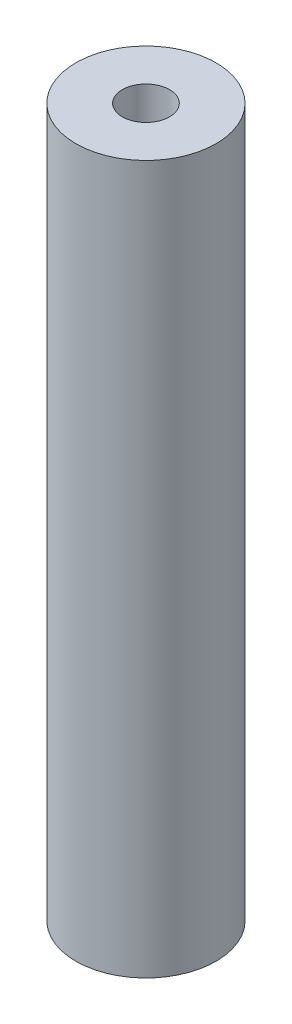
SolidWorks part; units mm, degrees
ref_plane "Front Plane" through (0, 0, 0) normal (0, 0, 1) x (1, 0, 0)
ref_plane "Top Plane" through (0, 0, 0) normal (0, 1, 0) x (1, 0, 0)
ref_plane "Right Plane" through (0, 0, 0) normal (1, 0, 0) x (0, 0, -1)
sketch "Sketch1" plane through (0, 0, 0) normal (0, 1, 0) x (1, 0, 0)
  circle A0 centre (0, 0) radius 2.97
  circle A1 centre (0, 0) radius 1
  dimension "D1" = 5.94
  dimension "D2" = 2
extrude "Boss-Extrude1" add sketch "Sketch1" along normal blind 30
